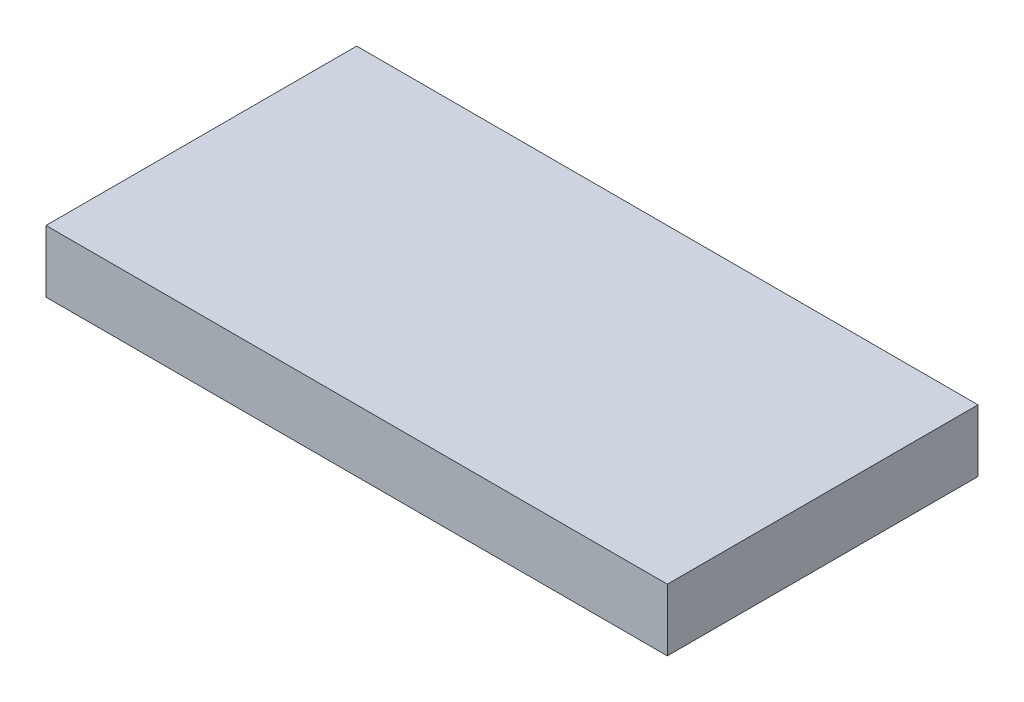
SolidWorks part; units mm, degrees
ref_plane "Front Plane" through (0, 0, 0) normal (0, 0, 1) x (1, 0, 0)
ref_plane "Top Plane" through (0, 0, 0) normal (0, 1, 0) x (1, 0, 0)
ref_plane "Right Plane" through (0, 0, 0) normal (1, 0, 0) x (0, 0, -1)
sketch "Sketch1" plane through (0, 0, 0) normal (0, 1, 0) x (1, 0, 0)
  line L1 (-16, -8) -> (16, -8)
  line L2 (-16, -8) -> (-16, 8)
  line L3 (-16, 8) -> (16, 8)
  line L4 (16, -8) -> (16, 8)
  line L5 (-16, -8) -> (16, 8) construction
  line L6 (-16, 8) -> (16, -8) construction
  point P0 (0, 0)
  dimension "D1" = 32
  dimension "D2" = 16
extrude "Boss-Extrude1" add sketch "Sketch1" along normal blind 3.2
